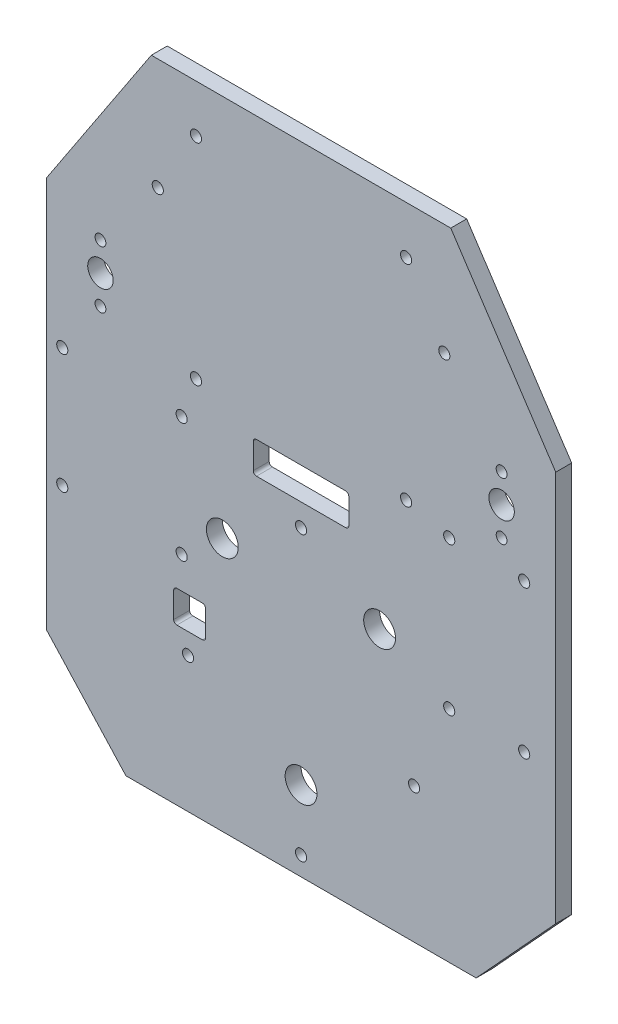
SolidWorks part; units mm, degrees
ref_plane "Plan de face" through (0, 0, 0) normal (1, 0, 0) x (0, 1, 0)
ref_plane "Plan de dessus" through (0, 0, 0) normal (0, 0, 1) x (0, 1, 0)
ref_plane "Plan de droite" through (0, 0, 0) normal (0, 1, 0) x (-1, 0, 0)
sketch "Esquisse1" plane through (0, 0, 0) normal (0, 0, 1) x (0, 1, 0)
  line L0 (0, 0) -> (-150.5414, 0) construction
  line L1 (-100, -80) -> (100, -80)
  line L2 (-100, -80) -> (-100, 80)
  line L3 (-100, 80) -> (100, 80)
  line L5 (-100, -80) -> (100, 80) construction
  line L6 (-100, 80) -> (100, -80) construction
  line L12 (-31, 38.8179) -> (-31, 42.3315) construction
  line L13 (-51, 40) -> (-41, 40)
  line L17 (-51, 40) -> (-51, 30)
  line L18 (-51, 30) -> (-41, 30)
  line L19 (-41, 40) -> (-41, 30)
  line L21 (-31.059, 37.5) -> (-30.571, 37.5) construction
  line L22 (-31, -46.5413) -> (-34.2714, -46.5413) construction
  line L28 (100, 80) -> (100, -80)
  line L30 (2, 15) -> (12, 15)
  line L31 (2, 15) -> (2, -15)
  line L32 (2, -15) -> (12, -15)
  line L33 (12, 15) -> (12, -15)
  circle A0 centre (-75, 0) radius 5
  circle A1 centre (-57.5, 35.5) radius 1.75
  circle A2 centre (-57.5, -35.5) radius 1.75
  circle A3 centre (65, 45) radius 1.75
  circle A4 centre (65, -45) radius 1.75
  circle A5 centre (-31, 37.5) radius 1.75
  circle A6 centre (-31, 75) radius 1.75
  circle A7 centre (6.5, 75) radius 1.75
  circle A8 centre (6.5, 37.5) radius 1.75
  circle A9 centre (-31, -46.5413) radius 1.75
  circle A10 centre (-31, -70.0913) radius 1.75
  circle A11 centre (15.5, -46.5413) radius 1.75
  circle A12 centre (15.5, -70.0913) radius 1.75
  circle A13 centre (-4.9993, 0) radius 1.75
  circle A16 centre (85, 33) radius 1.75
  circle A17 centre (85.0012, -33) radius 1.75
  circle A18 centre (19, 33) radius 1.75
  circle A19 centre (19.0012, -33) radius 1.75
  point P0 (0, 0)
  dimension "D3" = 10
  dimension "D9" = 3.5
  dimension "D10" = 35.5
  dimension "D11" = 17.5
  dimension "D5" = 3.5
  dimension "D6" = 45
  dimension "D7" = 15
  dimension "D16" = 37.5
  dimension "D17" = 37.5
  dimension "D18" = 37.5
  dimension "D19" = 3.5
  dimension "D20" = 3.5
  dimension "D21" = 3.5
  dimension "D22" = 3.5
  dimension "D23" = 10
  dimension "D24" = 5
  dimension "D25" = 3.5
  dimension "D26" = 3.5
  dimension "D27" = 3.5
  dimension "D28" = 3.5
  dimension "D29" = 46.5
  dimension "D30" = 46.5
  dimension "D31" = 23.55
  dimension "D32" = 23.55
  dimension "D35" = 3.5
  dimension "D36" = 3.5
  dimension "D41" = 66
  dimension "D42" = 66
  dimension "D47" = 3.5
  dimension "D48" = 3.5
  dimension "D50" = 66
  dimension "D52" = 33
  dimension "D33" = 14.9988
  dimension "D34" = 3.5
  dimension "D40" = 66
  dimension "D1" = 200
  dimension "D2" = 160
  dimension "D4" = 25
  dimension "D8" = 6.5
  dimension "D12" = 10
  dimension "D13" = 10
  dimension "D14" = 40
  dimension "D15" = 37.5
  dimension "D37" = 15
  dimension "D38" = 15
  dimension "D39" = 10
  dimension "D43" = 102
extrude "Boss.-Extru.1" add sketch "Esquisse1" along normal blind 5
fillet "Congé2" radius 1 8 edges at (-30, -51, 2.5) (-30, -41, 2.5) (-40, -41, 2.5) (-40, -51, 2.5) (15, 2, 2.5) (15, 12, 2.5) (-15, 12, 2.5) (-15, 2, 2.5)
sketch "Esquisse2" plane through (0, 0, 5) normal (0, 0, 1) x (1, 0, 0)
  line L0 (-110, 40) -> (0, 160)
  line L1 (0, 160) -> (110, 40)
  line L2 (110, 40) -> (110, -40)
  line L3 (110, -40) -> (0, -160)
  line L5 (0, -160) -> (-110, -40)
  line L6 (-110, -40) -> (-110, 40)
  line L14 (-573.5804, 598.1671) -> (-698.6982, -488.0825)
  line L15 (-80, 100) -> (-80, -100) construction
  line L16 (80, -100) -> (80, 100) construction
  line L17 (0, 70) -> (0, 33.5097) construction
  line L18 (-698.6982, -488.0825) -> (684.3, -647.3807)
  line L19 (0, 0) -> (-114.7759, 0) construction
  line L20 (684.3, -647.3807) -> (762.9047, 702.4319)
  line L21 (762.9047, 702.4319) -> (-573.5804, 598.1671)
  dimension "D1" = 160
  dimension "D2" = 160
  dimension "D3" = 40
  dimension "D4" = 40
  dimension "D5" = 40
  dimension "D6" = 40
  dimension "D7" = 110
extrude "Enlèv. mat.-Extru.1" cut sketch "Esquisse2" against normal through all
sketch "Esquisse3" plane through (0, 0, 0) normal (0, 0, 1) x (0, 1, 0)
  circle A0 centre (-94.0015, 0.004) radius 1.75
extrude "Trou cuve direction" cut sketch "Esquisse3" along normal through all
sketch "Esquisse4" plane through (0, 0, 5) normal (0, 0, 1) x (1, 0, 0)
  line L0 (-82.024, 47.0385) -> (-45.024, 103.0385)
  line L1 (-45.024, 103.0385) -> (-83.024, 103.0385)
  line L2 (-83.024, 103.0385) -> (-83.024, 47.0385)
  line L3 (-83.024, 47.0385) -> (-82.024, 47.0385)
  line L4 (82.016, 47.0385) -> (45.016, 103.0385)
  line L5 (45.016, 103.0385) -> (83.016, 103.0385)
  line L6 (83.016, 103.0385) -> (83.016, 47.0385)
  line L7 (83.016, 47.0385) -> (82.016, 47.0385)
  circle A0 centre (-63.004, 23.7385) radius 1.7
  circle A1 centre (-63.004, 41.7385) radius 1.7
  circle A2 centre (62.996, 23.7385) radius 1.7
  circle A3 centre (62.996, 41.7385) radius 1.7
  circle A4 centre (-63.004, 32.7385) radius 4
  circle A5 centre (62.996, 32.7385) radius 4
  circle A6 centre (-24.724, -20.2615) radius 5
  circle A7 centre (24.676, -20.2615) radius 5
extrude "Pointe avant, trous berceau et cables" cut sketch "Esquisse4" against normal through all
